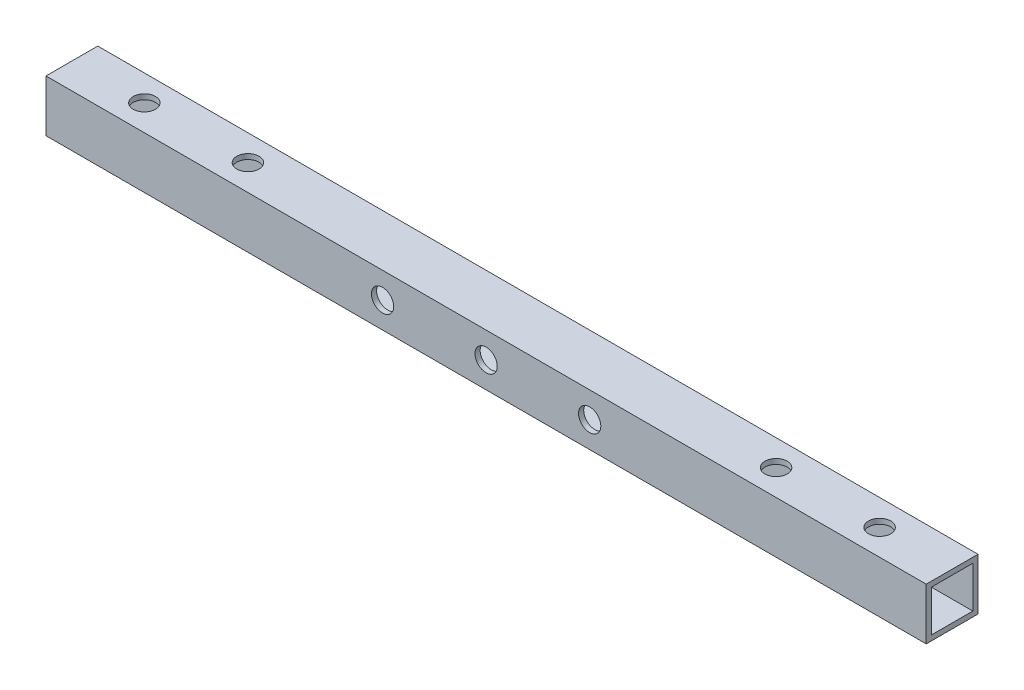
SolidWorks part; units mm, degrees
material "5052-H34"
ref_plane "正面" through (0, 0, 0) normal (0, 0, 1) x (1, 0, 0)
ref_plane "平面" through (0, 0, 0) normal (0, 1, 0) x (1, 0, 0)
ref_plane "右側面" through (0, 0, 0) normal (1, 0, 0) x (0, 0, -1)
sketch "ｽｹｯﾁ2" plane through (0, 0, 0) normal (1, 0, 0) x (0, 0, -1)
  line L1 (0, 0) -> (10, 0)
  line L2 (0, 0) -> (0, 10)
  line L3 (0, 10) -> (10, 10)
  line L4 (10, 0) -> (10, 10)
  dimension "D1" = 10
  dimension "D2" = 10
extrude "押し出し-薄板1" add sketch "ｽｹｯﾁ2" along normal blind 170 thin thin type one direction reverse wall 1
sketch "ｽｹｯﾁ3" plane through (0, 10, 0) normal (0, 1, 0) x (1, 0, 0)
  line L0 (0, 5) -> (170, 5) construction
  line L1 (0, 10) -> (0, 0) construction
  line L2 (170, 10) -> (170, 0) construction
  line L3 (85, 10) -> (85, 0) construction
  line L4 (170, 10) -> (0, 10) construction
  line L5 (170, 0) -> (0, 0) construction
  circle A2 centre (14, 5) radius 2.15
  circle A3 centre (34, 5) radius 2.15
  circle A4 centre (136, 5) radius 2.15
  circle A5 centre (156, 5) radius 2.15
  dimension "D1" = 4.3
  dimension "D3" = 102
  dimension "D4" = 20
extrude "ｶｯﾄ - 押し出し1" cut sketch "ｽｹｯﾁ3" against normal up to surface (10 mm away) up to face at (85, 0, -5)
sketch "ｽｹｯﾁ4" plane through (0, 0, 0) normal (0, 0, 1) x (1, 0, 0)
  line L0 (85, 10) -> (85, 0) construction
  line L1 (170, 10) -> (0, 10) construction
  line L2 (170, 0) -> (0, 0) construction
  line L3 (85, 5) -> (105, 5) construction
  circle A0 centre (105, 5) radius 2.15
  circle A1 centre (85, 5) radius 2.15
  circle A2 centre (65, 5) radius 2.15
  dimension "D1" = 4.3
  dimension "D2" = 20
extrude "ｶｯﾄ - 押し出し2" cut sketch "ｽｹｯﾁ4" against normal through all
